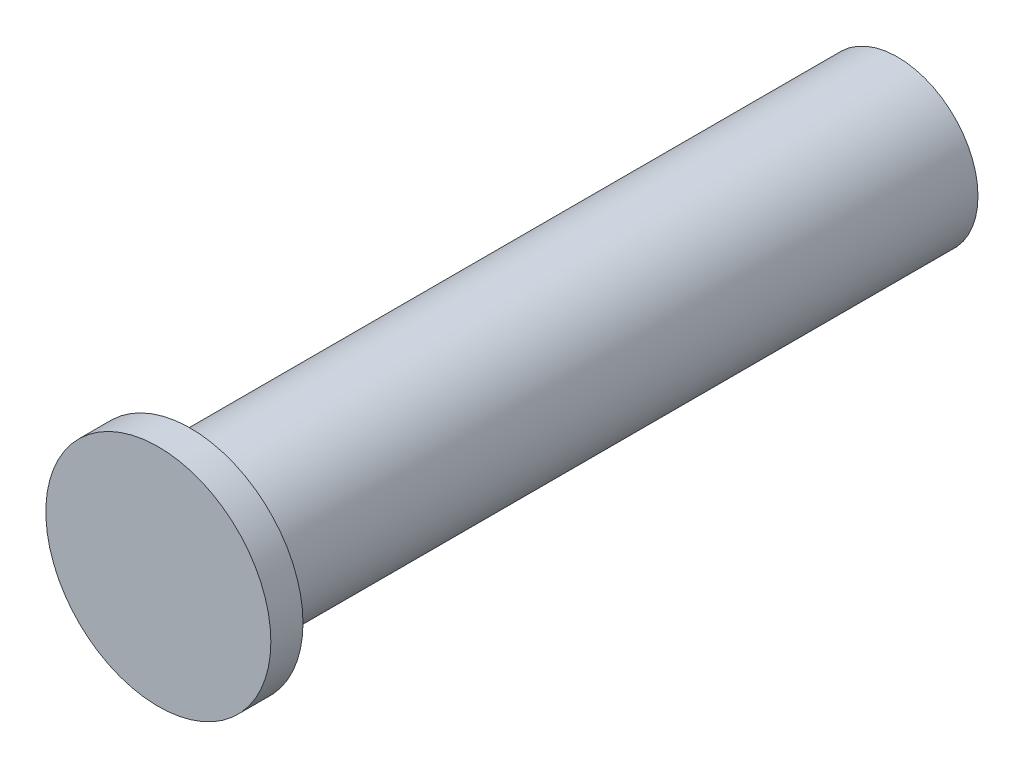
SolidWorks part; units mm, degrees
ref_plane "Front Plane" through (0, 0, 0) normal (0, 0, 1) x (1, 0, 0)
ref_plane "Top Plane" through (0, 0, 0) normal (0, 1, 0) x (1, 0, 0)
ref_plane "Right Plane" through (0, 0, 0) normal (1, 0, 0) x (0, 0, -1)
sketch "Sketch1" plane through (0, 0, 0) normal (0, 0, 1) x (1, 0, 0)
  circle A0 centre (0, 0) radius 12.5
  dimension "D1" = 25
extrude "Boss-Extrude1" add sketch "Sketch1" along normal blind 110
sketch "Sketch2" plane through (0, 0, 110) normal (0, 0, 1) x (1, 0, 0)
  circle A0 centre (0, 0) radius 17.5
  dimension "D1" = 35
extrude "Boss-Extrude2" add sketch "Sketch2" along normal blind 5
